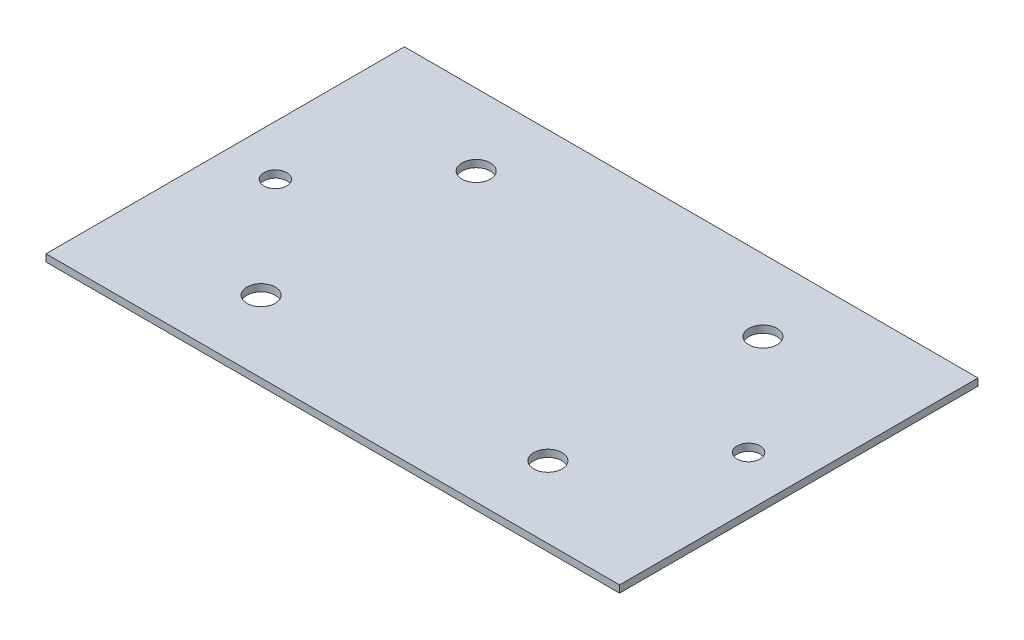
SolidWorks part; units mm, degrees
ref_plane "Front Plane" through (0, 0, 0) normal (0, 0, 1) x (1, 0, 0)
ref_plane "Top Plane" through (0, 0, 0) normal (0, 1, 0) x (1, 0, 0)
ref_plane "Right Plane" through (0, 0, 0) normal (1, 0, 0) x (0, 0, -1)
sketch "Sketch1" plane through (0, 0, 0) normal (0, 1, 0) x (1, 0, 0)
  line L0 (40, 50) -> (40, 0) construction
  line L1 (0, 0) -> (80, 0)
  line L2 (0, 0) -> (0, 50)
  line L3 (0, 50) -> (80, 50)
  line L4 (80, 0) -> (80, 50)
  line L5 (0, 25) -> (80, 25) construction
  circle A0 centre (20, 40) radius 1.975
  circle A1 centre (60, 40) radius 1.975
  circle A2 centre (20, 10) radius 1.975
  circle A3 centre (60, 10) radius 1.975
  circle A4 centre (7, 25) radius 1.6
  circle A5 centre (73, 25) radius 1.6
  dimension "D7" = 3.2
  dimension "D10" = 3.95
  dimension "D1" = 80
  dimension "D2" = 50
  dimension "D3" = 20
  dimension "D4" = 20
  dimension "D5" = 15
  dimension "D6" = 15
  dimension "D8" = 7
  dimension "D9" = 7
extrude "Boss-Extrude1" add sketch "Sketch1" along normal blind 1
equation "\"D4@Sketch1\"=\"D3@Sketch1\""
equation "\"D6@Sketch1\"=\"D5@Sketch1\""
